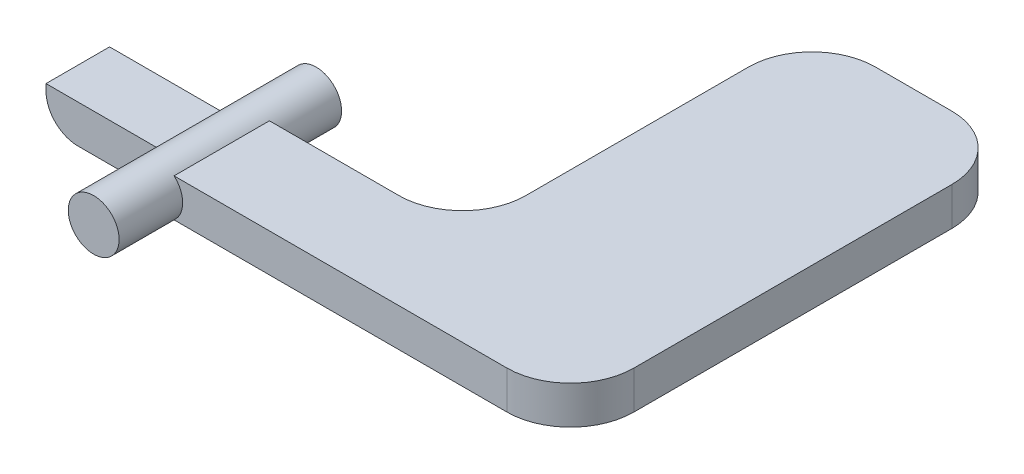
SolidWorks part; units mm, degrees
ref_plane "Front Plane" through (0, 0, 0) normal (0, 0, 1) x (1, 0, 0)
ref_plane "Top Plane" through (0, 0, 0) normal (0, 1, 0) x (1, 0, 0)
ref_plane "Right Plane" through (0, 0, 0) normal (1, 0, 0) x (0, 0, -1)
sketch "Sketch9" plane through (0, 0, 0) normal (0, 1, 0) x (1, 0, 0)
  line L1 (0, -7.5) -> (65, -7.5)
  line L2 (65, -7.5) -> (65, 62.5)
  line L3 (65, 62.5) -> (33, 62.5)
  line L4 (33, 62.5) -> (33, 7.5)
  line L5 (33, 7.5) -> (0, 7.5)
  line L6 (0, 7.5) -> (0, -7.5) construction
  line L7 (0, 7.5) -> (0, 5)
  line L8 (0, 5) -> (-20, 5)
  line L9 (-20, 5) -> (-20, -5)
  line L10 (-20, -5) -> (0, -5)
  line L11 (0, -5) -> (0, -7.5)
  dimension "D1" = 65
  dimension "D2" = 32
  dimension "D3" = 15
  dimension "D4" = 10
  dimension "D5" = 70
  dimension "D6" = 20
  dimension "D7" = 2.5
extrude "Boss-Extrude4" add sketch "Sketch9" along normal mid plane 6
sketch "Sketch10" plane through (0, 0, 7.5) normal (0, 0, 1) x (1, 0, 0)
  circle A0 centre (0, 0) radius 4
  dimension "D1" = 8
extrude "Boss-Extrude5" add sketch "Sketch10" along normal blind 10 and the other way blind 25
fillet "Fillet4" radius 10 4 edges at (33, 0, -7.5) (33, 0, -62.5) (65, 0, -62.5) (65, 0, 7.5)
fillet "Fillet5" radius 5 1 edges at (-20, -3, 0)
